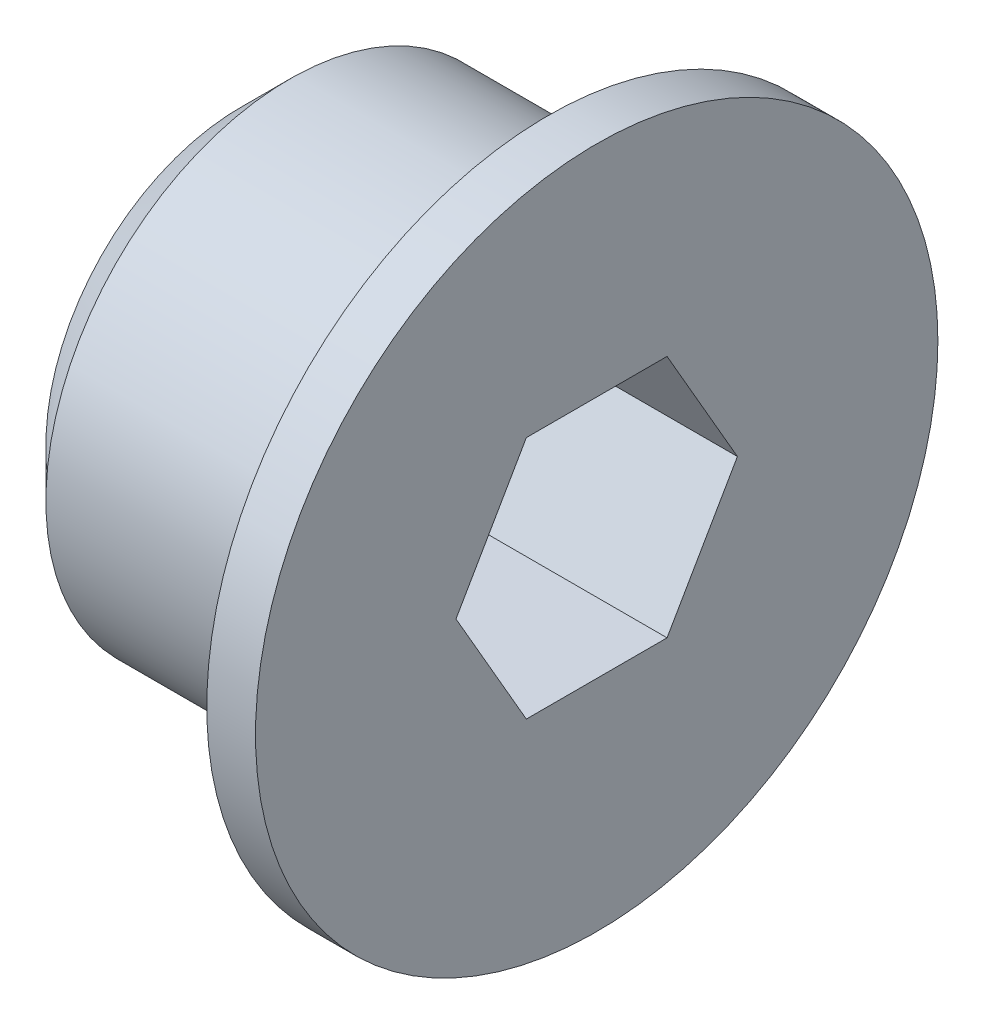
SolidWorks part; units mm, degrees
material "ABS"
ref_plane "前视基准面" through (0, 0, 0) normal (0, 0, 1) x (1, 0, 0)
ref_plane "上视基准面" through (0, 0, 0) normal (0, 1, 0) x (1, 0, 0)
ref_plane "右视基准面" through (0, 0, 0) normal (1, 0, 0) x (0, 0, -1)
other "Configuration Table"
sketch "草图1" plane through (0, 0, 0) normal (1, 0, 0) x (0, 0, -1)
  line L1 (2.8868, 0) -> (1.4434, 2.5)
  line L2 (1.4434, 2.5) -> (-1.4434, 2.5)
  line L3 (-1.4434, 2.5) -> (-2.8868, 0)
  line L4 (-2.8868, 0) -> (-1.4434, -2.5)
  line L5 (-1.4434, -2.5) -> (1.4434, -2.5)
  line L6 (1.4434, -2.5) -> (2.8868, 0)
  circle A0 centre (0, 0) radius 2.5 construction
  circle A1 centre (0, 0) radius 5
  dimension "D1" = 5
  dimension "D2" = 10
extrude "凸台-拉伸1" add sketch "草图1" along normal blind 6.3
sketch "草图2" plane through (6.3, 0, 0) normal (1, 0, 0) x (0, 0, -1)
  line L6 (2.8868, 0) -> (1.4434, 2.5)
  line L7 (1.4434, -2.5) -> (2.8868, 0)
  line L8 (-1.4434, -2.5) -> (1.4434, -2.5)
  line L9 (-2.8868, 0) -> (-1.4434, -2.5)
  line L10 (-1.4434, 2.5) -> (-2.8868, 0)
  line L11 (1.4434, 2.5) -> (-1.4434, 2.5)
  line L12 (2.8868, 0) -> (1.4434, 2.5)
  line L13 (1.4434, -2.5) -> (2.8868, 0)
  line L14 (-1.4434, -2.5) -> (1.4434, -2.5)
  line L15 (-2.8868, 0) -> (-1.4434, -2.5)
  line L16 (-1.4434, 2.5) -> (-2.8868, 0)
  line L17 (1.4434, 2.5) -> (-1.4434, 2.5)
  circle A0 centre (0, 0) radius 7
  dimension "D2" = 14
  dimension "D1" = 0
extrude "凸台-拉伸2" add sketch "草图2" along normal blind 1
chamfer "倒角1" distance 1 angle 45 1 edges at (0, 0, -5)
